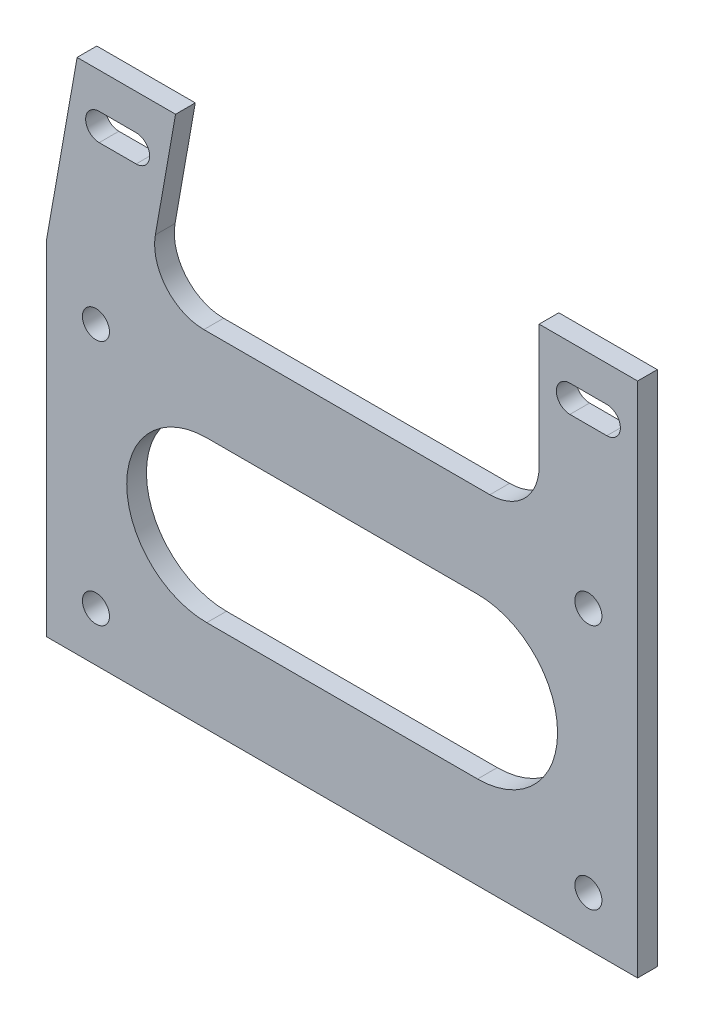
SolidWorks part; units mm, degrees
ref_plane "Front Plane" through (0, 0, 0) normal (0, 0, 1) x (1, 0, 0)
ref_plane "Top Plane" through (0, 0, 0) normal (0, 1, 0) x (1, 0, 0)
ref_plane "Right Plane" through (0, 0, 0) normal (1, 0, 0) x (0, 0, -1)
sketch "Sketch1" plane through (0, 0, 0) normal (0, 0, 1) x (1, 0, 0)
  line L0 (-60, 35) -> (-53.8286, 70)
  line L1 (-60, -35) -> (60, -35)
  line L2 (-60, -35) -> (-60, 35)
  line L3 (-28.0825, 35) -> (30, 35)
  line L4 (60, -35) -> (60, 35)
  line L5 (-60, -35) -> (60, 35) construction
  line L6 (-60, 35) -> (60, -35) construction
  line L8 (60, 35) -> (60, 70)
  line L9 (60, 70) -> (40, 70)
  line L10 (40, 45) -> (40, 70)
  line L11 (-53.8286, 70) -> (-33.8286, 70)
  line L12 (-33.8286, 70) -> (-37.9305, 46.7365)
  line L13 (-35.5918, 60) -> (-55.5918, 60) construction
  line L14 (40, 60) -> (60, 60) construction
  line L15 (-27.5, 16.0417) -> (-27.5, 16.25)
  line L16 (-49.3418, 57.25) -> (-41.8418, 57.25)
  line L17 (-27.5, -16.25) -> (27.5, -16.25)
  line L18 (-49.3418, 62.75) -> (-41.8418, 62.75)
  line L19 (-27.5, -16.25) -> (-27.5, -16.0417)
  line L20 (-49.3418, 57.25) -> (-41.8418, 62.75) construction
  line L21 (-49.3418, 62.75) -> (-41.8418, 57.25) construction
  line L22 (46.25, 57.25) -> (53.75, 57.25)
  line L23 (-27.5, 16.25) -> (27.5, 16.25)
  line L24 (46.25, 62.75) -> (53.75, 62.75)
  line L25 (27.5, -16.25) -> (27.5, -16.0417)
  line L26 (46.25, 57.25) -> (53.75, 62.75) construction
  line L27 (46.25, 62.75) -> (53.75, 57.25) construction
  line L28 (-27.5, -16.25) -> (27.5, 16.25) construction
  line L29 (-27.5, 16.25) -> (27.5, -16.25) construction
  line L30 (27.5, 16.0417) -> (27.5, 16.25)
  circle A0 centre (-50, 25) radius 2.75
  circle A1 centre (-50, -25) radius 2.75
  circle A2 centre (50, 25) radius 2.75
  circle A3 centre (50, -25) radius 2.75
  arc A4 (-49.3418, 62.75) -> (-49.3418, 57.25) centre (-49.3418, 60) ccw
  arc A5 (-41.8418, 57.25) -> (-41.8418, 62.75) centre (-41.8418, 60) ccw
  arc A6 (46.25, 62.75) -> (46.25, 57.25) centre (46.25, 60) ccw
  arc A7 (53.75, 57.25) -> (53.75, 62.75) centre (53.75, 60) ccw
  arc A8 (27.5, -16.25) -> (27.5, 16.25) centre (27.5, 0) ccw
  arc A9 (-27.5, 16.25) -> (-27.5, -16.25) centre (-27.5, 0) ccw
  arc A10 (-13.1856, 7.6916) -> (-13.2657, 7.8388) centre (-27.5, 0) ccw
  arc A11 (-13.2657, -7.8388) -> (-13.1856, -7.6916) centre (-27.5, 0) ccw
  arc A12 (13.1856, -7.6916) -> (13.2657, -7.8388) centre (27.5, 0) ccw
  arc A13 (13.2657, 7.8388) -> (13.1856, 7.6916) centre (27.5, 0) ccw
  arc A14 (-28.0825, 35) -> (-37.9305, 46.7365) centre (-28.0825, 45) cw
  arc A15 (40, 45) -> (30, 35) centre (30, 45) cw
  point P0 (0, 0)
  point P17 (-45.5918, 60)
  point P28 (50, 60)
  point P36 (0, 0)
  dimension "D3" = 5.5
  dimension "D4" = 10
  dimension "D5" = 10
  dimension "D6" = 10
  dimension "D7" = 10
  dimension "D16" = 2.75
  dimension "D17" = 2.75
  dimension "D18" = 55
  dimension "D2" = 10
  dimension "D9" = 10
  dimension "D1" = 120
  dimension "D8" = 20
  dimension "D10" = 80
  dimension "D11" = 35
  dimension "D12" = 20
  dimension "D13" = 7.5
  dimension "D14" = 5.5
  dimension "D15" = 25
  dimension "D19" = 32.5
  dimension "D20" = 58.0825
  dimension "D21" = 105
  dimension "D22" = 70
extrude "Boss-Extrude1" add sketch "Sketch1" along normal blind 4 contours L1 L4 L3 L2 A9 L23 A8 L17 A3 A2 A1 A0 | L10 L3 L8 L9 A7 L22 A6 L24 | L12 L11 L0 L3 A5 L16 A4 L18
